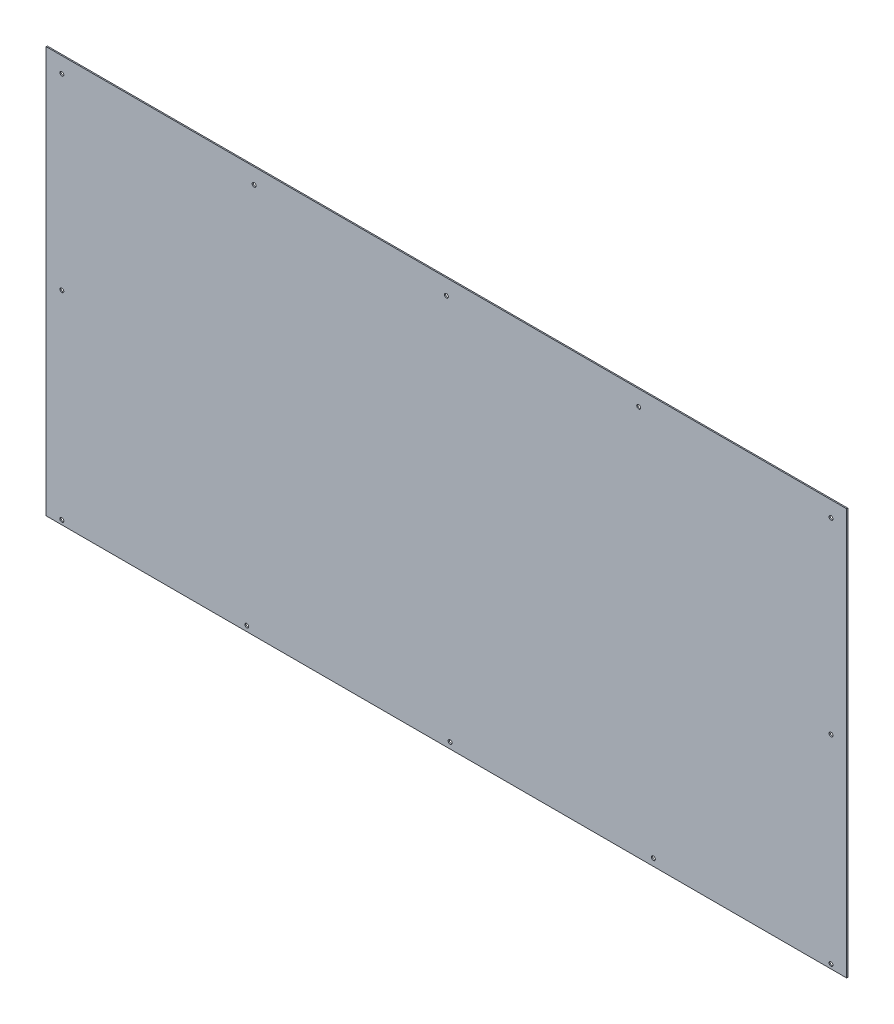
SolidWorks part; units mm, degrees
ref_plane "Alzado" through (0, 0, 0) normal (0, 0, 1) x (1, 0, 0)
ref_plane "Planta" through (0, 0, 0) normal (0, 1, 0) x (1, 0, 0)
ref_plane "Vista lateral" through (0, 0, 0) normal (1, 0, 0) x (0, 0, -1)
sketch "Croquis1" plane through (0, 0, 0) normal (0, 0, 1) x (1, 0, 0)
  line L1 (-650, 330) -> (650, 330)
  line L2 (-650, 330) -> (-650, -330)
  line L3 (-650, -330) -> (650, -330)
  line L4 (650, 330) -> (650, -330)
  line L5 (-650, 330) -> (650, -330) construction
  line L6 (-650, -330) -> (650, 330) construction
  point P0 (0, 0)
  dimension "D1" = 660
  dimension "D2" = 1300
extrude "Saliente-Extruir1" add sketch "Croquis1" along normal blind 1.9
sketch "Croquis2" plane through (0, 0, 1.9) normal (0, 0, 1) x (1, 0, 0)
  line L0 (650, 330) -> (-650, 330) construction
  line L1 (-624.6, -304.6) -> (624.6, -304.6) construction
  line L2 (-624.6, -304.6) -> (-624.6, 304.6) construction
  line L3 (-624.6, 304.6) -> (624.6, 304.6) construction
  line L4 (624.6, -304.6) -> (624.6, 304.6) construction
  line L5 (-624.6, -304.6) -> (624.6, 304.6) construction
  line L6 (-624.6, 304.6) -> (624.6, -304.6) construction
  line L7 (-650, 330) -> (-650, -330) construction
  line L8 (0, 0) -> (0, 304.6) construction
  line L9 (0, 0) -> (159.2342, 0) construction
  line L10 (-624.6, 304.6) -> (0, 304.6) construction
  line L11 (0, 304.6) -> (-312.3, 304.6) construction
  line L12 (0, 304.6) -> (624.6, 304.6) construction
  line L13 (624.6, 304.6) -> (312.3, 304.6) construction
  line L14 (-624.6, 0) -> (0, 0) construction
  line L15 (-624.6, -330) -> (-624.6, -323) construction
  line L16 (-650, -330) -> (650, -330) construction
  circle A0 centre (-624.6, 304.6) radius 3.175
  circle A1 centre (0, 304.6) radius 3.175
  circle A2 centre (624.6, 304.6) radius 3.175
  circle A3 centre (-312.3, 304.6) radius 3.175
  circle A4 centre (312.3, 304.6) radius 3.175
  circle A5 centre (-624.6, 0) radius 3.175
  circle A6 centre (624.6, 0) radius 3.175
  circle A7 centre (-624.6, -323) radius 3.175
  circle A8 centre (624.6, -323) radius 3.175
  point P0 (0, 0)
  dimension "D3" = 6.35
  dimension "D4" = 6.35
  dimension "D5" = 6.35
  dimension "D6" = 6.35
  dimension "D7" = 6.35
  dimension "D8" = 6.35
  dimension "D1" = 25.4
  dimension "D2" = 25.4
  dimension "D9" = 7
extrude "Cortar-Extruir2" cut sketch "Croquis2" against normal blind 6.35
sketch "Croquis4" plane through (0, 0, 0) normal (0, 0, -1) x (-1, 0, 0)
  line L0 (294.3, -337) -> (294.3, -321.4162) construction
  line L1 (624.6, -323) -> (-522.431, -317.5) construction
  line L2 (599.2, -317.5) -> (-599.2, -317.5) construction
  line L3 (294.3, -321.4162) -> (324.3, -321.5601) construction
  line L4 (-36, -337) -> (-36, -319.8324) construction
  line L5 (-36, -319.8324) -> (-6, -319.9763) construction
  line L6 (-366.3, -337) -> (-366.3, -318.2486) construction
  line L7 (-366.3, -318.2486) -> (-336.3, -318.3925) construction
  circle A0 centre (324.3, -321.5601) radius 3.175
  circle A1 centre (-6, -319.9763) radius 3.175
  circle A2 centre (-336.3, -318.3925) radius 3.175
  point P16 (-36, -328.4162)
  dimension "D4" = 6.35
  dimension "D5" = 6.35
  dimension "D6" = 6.35
  dimension "D1" = 30
  dimension "D2" = 30
  dimension "D3" = 30
extrude "Cortar-Extruir3" cut sketch "Croquis4" against normal blind 10
